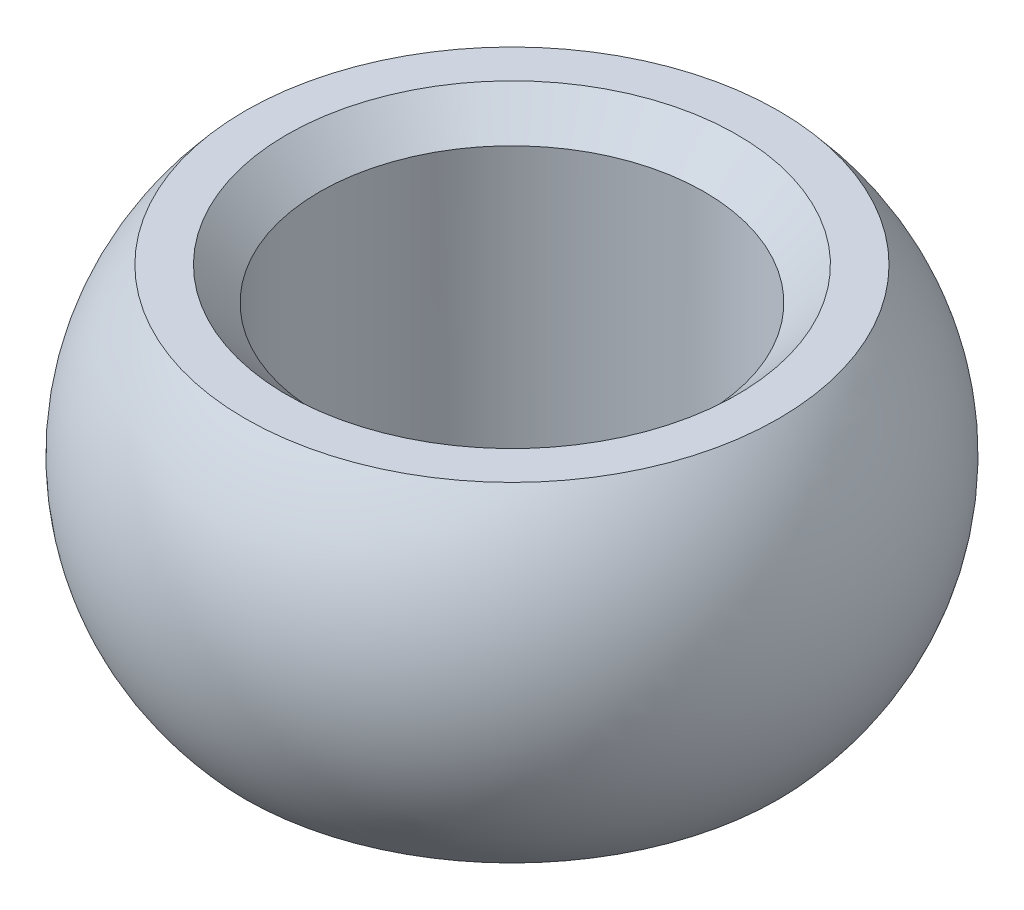
SolidWorks part; units mm, degrees
material "Custom Plastic"
ref_plane "Front Plane" through (0, 0, 0) normal (0, 0, 1) x (1, 0, 0)
ref_plane "Top Plane" through (0, 0, 0) normal (0, 1, 0) x (1, 0, 0)
ref_plane "Right Plane" through (0, 0, 0) normal (1, 0, 0) x (0, 0, -1)
sketch "Sketch1" plane through (0, 0, 0) normal (0, 0, 1) x (1, 0, 0)
  line L0 (0, -441.215) -> (0, 21619.535) construction
  line L1 (17.5, 15) -> (24.2705, 15)
  line L2 (17.5, 15) -> (17.5, -15)
  line L3 (17.5, -15) -> (24.2705, -15)
  arc A0 (24.2705, 15) -> (24.2705, -15) centre (7.5, 0) cw
  point P6 (17.5, 0)
  point P7 (30, 0)
  dimension "D1" = 30
  dimension "D2" = 22.5
  dimension "D3" = 17.5
  dimension "D4" = 60
revolve "Revolve1" add sketch "Sketch1" angle 360 about L0
chamfer "Chamfer1" distance 3 angle 45 2 edges at (17.5, 15, 0) (17.5, -15, 0)
